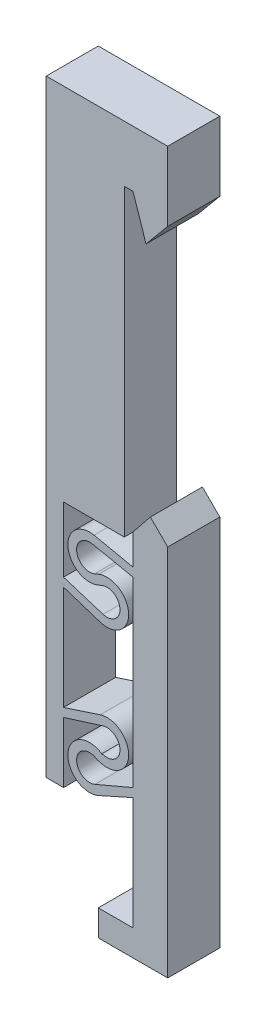
SolidWorks part; units mm, degrees
ref_plane "Front Plane" through (0, 0, 0) normal (0, 0, 1) x (1, 0, 0)
ref_plane "Top Plane" through (0, 0, 0) normal (0, 1, 0) x (1, 0, 0)
ref_plane "Right Plane" through (0, 0, 0) normal (1, 0, 0) x (0, 0, -1)
sketch "Sketch5" plane through (0, 0, 0) normal (0, 0, 1) x (1, 0, 0)
  line L0 (0, 31.5) -> (14, 31.5)
  line L1 (0, -55) -> (0, 55) construction
  line L2 (14, 31.5) -> (14, 23.5)
  line L3 (14, 23.5) -> (11.5, 20.5)
  line L4 (11.5, 20.5) -> (10, 25)
  line L5 (10, 25) -> (9, 25)
  line L6 (9, 25) -> (9, -10)
  line L7 (9, -10) -> (2, -10)
  line L8 (10, -13.5) -> (10, -34.5)
  line L9 (2, -30.5) -> (2, -18.5)
  line L10 (2, -31.5) -> (2, -38.5)
  line L11 (55, 0) -> (-55, 0) construction
  line L12 (0, -38.5) -> (0, 31.5)
  line L13 (6, -48.5) -> (6, -51.5)
  line L14 (6, -51.5) -> (14, -51.5)
  line L15 (14, -51.5) -> (14, -8.5)
  line L16 (14, -8.5) -> (12, -6.5)
  line L17 (12, -6.5) -> (10, -9)
  line L18 (10, -9) -> (10, -12.5)
  line L19 (6.2254, -29.123) -> (2, -30.5)
  line L20 (6.55, -30.0691) -> (2, -31.5)
  line L21 (10, -48.5) -> (6, -48.5)
  line L22 (6.2254, -19.877) -> (2, -18.5)
  line L23 (6.55, -18.9309) -> (2, -17.5)
  line L24 (5.5162, -11.5539) -> (10, -12.5)
  line L25 (5.3031, -12.5309) -> (10, -13.5)
  line L26 (2, -10) -> (2, -17.5)
  line L27 (6.0385, -15.1923) -> (5.5769, -15.3846)
  line L28 (6.4369, -32.8903) -> (6.5365, -33.0279)
  line L29 (5.9219, -33.8168) -> (6.0615, -33.8172)
  line L30 (5.6131, -36.369) -> (10, -34.5)
  line L31 (6.0218, -37.2816) -> (10, -35.5)
  line L32 (10, -35.5) -> (10, -48.5)
  line L33 (6.4231, -16.1154) -> (5.9615, -16.3077)
  line L36 (2, -38.5) -> (0, -38.5)
  arc A0 (6.55, -18.9309) -> (6.4231, -16.1154) centre (7, -17.5) ccw
  arc A1 (6.2254, -19.877) -> (6.0385, -15.1923) centre (7, -17.5) ccw
  arc A2 (5.3031, -12.5309) -> (5.5769, -15.3846) centre (5, -14) ccw
  arc A3 (5.5162, -11.5539) -> (5.9615, -16.3077) centre (5, -14) ccw
  arc A4 (6.4369, -32.8903) -> (6.55, -30.0691) centre (7, -31.5) ccw
  arc A5 (6.0615, -33.8172) -> (6.2254, -29.123) centre (7, -31.5) ccw
  arc A6 (5.9219, -33.8168) -> (5.6131, -36.369) centre (5, -35) ccw
  arc A7 (6.5365, -33.0279) -> (6.0218, -37.2816) centre (5, -35) ccw
  dimension "D2" = 3
  dimension "D3" = 5
  dimension "D4" = 3
  dimension "D5" = 5
  dimension "D6" = 3
  dimension "D7" = 5
  dimension "D8" = 3
  dimension "D9" = 5
  dimension "D10" = 2
  dimension "D11" = 5
  dimension "D12" = 2
  dimension "D13" = 3
  dimension "D14" = 21.5
  dimension "D15" = 25
  dimension "D16" = 9
  dimension "D17" = 2
  dimension "D18" = 4
  dimension "D19" = 7.5
  dimension "D20" = 12
  dimension "D21" = 1
  dimension "D22" = 1
  dimension "D23" = 1
  dimension "D24" = 1
  dimension "D25" = 7.5
  dimension "D26" = 5
  dimension "D27" = 8
  dimension "D28" = 4
  dimension "D29" = 8
  dimension "D30" = 8
  dimension "D31" = 3
  dimension "D32" = 14
  dimension "D33" = 1
  dimension "D34" = 4.5
  dimension "D35" = 2.5
  dimension "D36" = 8
  dimension "D37" = 35
  dimension "D38" = 3.5
  dimension "D39" = 2.5
  dimension "D40" = 2
  dimension "D41" = 2
  dimension "D42" = 43
  dimension "D43" = 1
  dimension "D44" = 1
  dimension "D45" = 1
  dimension "D46" = 3
  dimension "D47" = 21
  dimension "D48" = 7
  dimension "D49" = 70
  dimension "D50" = 1
  dimension "D51" = 10
extrude "Boss-Extrude4" add sketch "Sketch5" along normal blind 6 separate body
sketch "Sketch2" plane through (0, 0, 0) normal (1, 0, 0) x (0, 0, -1)
  line L0 (0, 7.7) -> (0, -7.7) construction
  line L1 (0, 30) -> (15, 30)
  line L2 (0, 30) -> (0, -25)
  line L3 (0, -25) -> (15, -25)
  line L4 (15, 30) -> (15, -25)
  line L5 (7.7, 0) -> (-7.7, 0) construction
  dimension "D1" = 15
  dimension "D2" = 55
  dimension "D3" = 25
